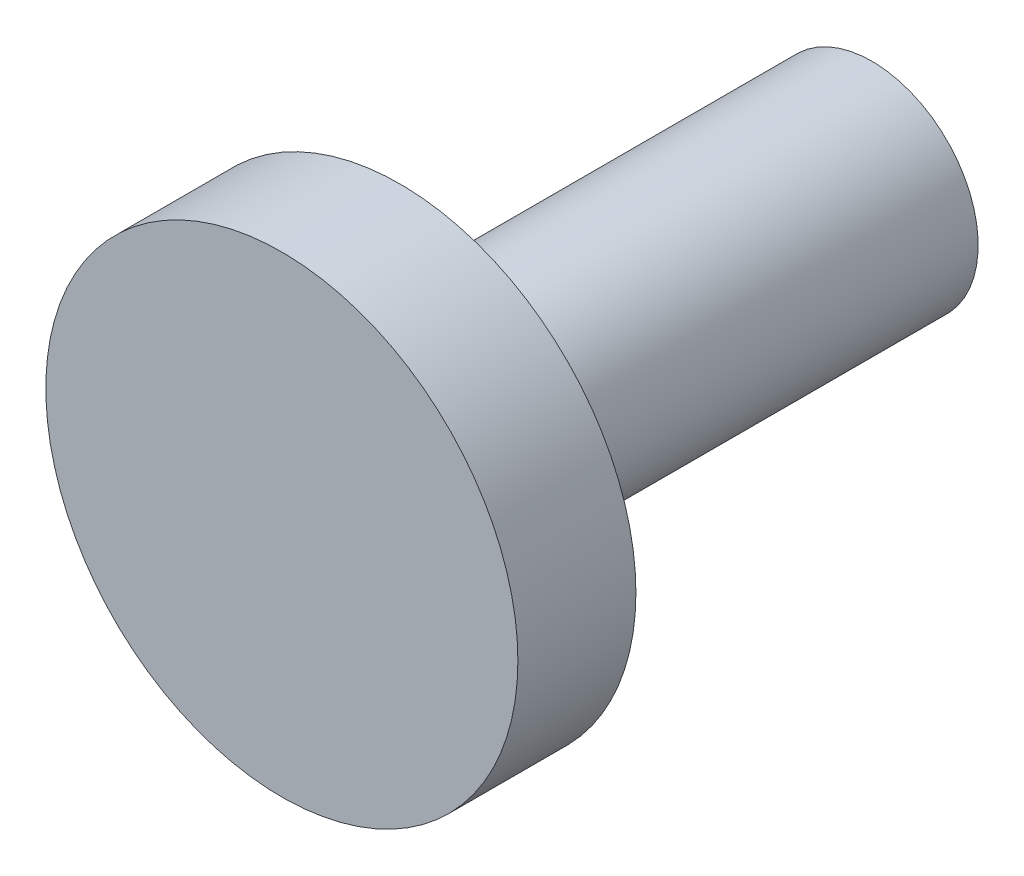
SolidWorks part; units mm, degrees
ref_plane "Front Plane" through (0, 0, 0) normal (0, 0, 1) x (1, 0, 0)
ref_plane "Top Plane" through (0, 0, 0) normal (0, 1, 0) x (1, 0, 0)
ref_plane "Right Plane" through (0, 0, 0) normal (1, 0, 0) x (0, 0, -1)
sketch "Sketch1" plane through (0, 0, 0) normal (0, 0, 1) x (1, 0, 0)
  circle A0 centre (0, 0) radius 5
  dimension "D1" = 10
extrude "Boss-Extrude1" add sketch "Sketch1" along normal blind 2.5
sketch "Sketch2" plane through (0, 0, 0) normal (0, 0, -1) x (-1, 0, 0)
  circle A0 centre (0, 0) radius 2.25
  dimension "D1" = 4.5
extrude "Boss-Extrude2" add sketch "Sketch2" along normal blind 10
sketch "Sketch3" plane through (0, 0, -10) normal (0, 0, -1) x (-1, 0, 0)
  circle A0 centre (0, 0) radius 1.25
  dimension "D1" = 2.5
extrude "Cut-Extrude1" cut sketch "Sketch3" against normal blind 10
